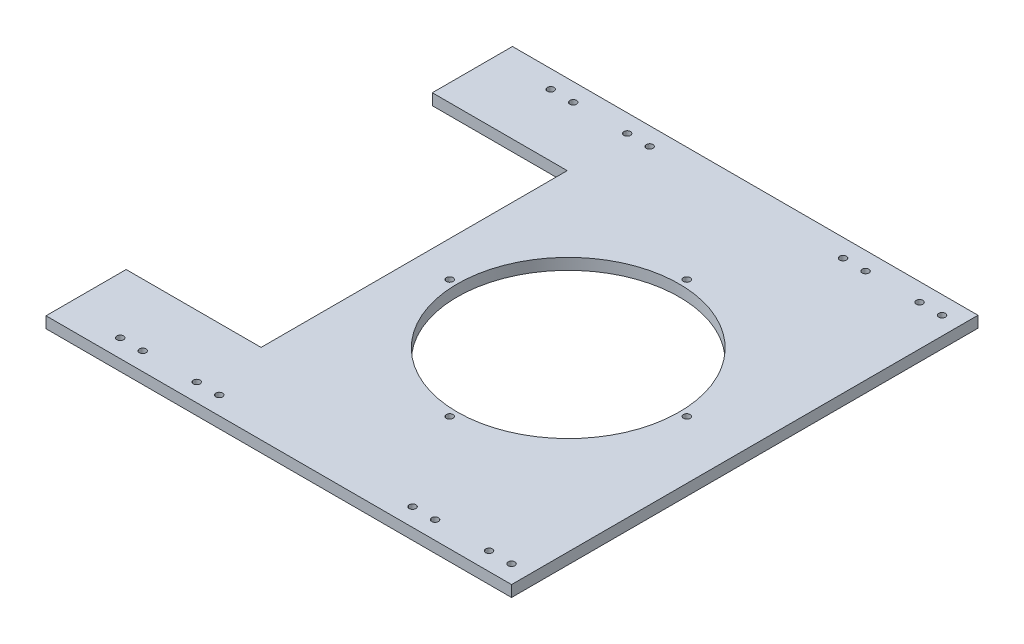
SolidWorks part; units mm, degrees
ref_plane "Front Plane" through (0, 0, 0) normal (0, 0, 1) x (1, 0, 0)
ref_plane "Top Plane" through (0, 0, 0) normal (0, 1, 0) x (1, 0, 0)
ref_plane "Right Plane" through (0, 0, 0) normal (1, 0, 0) x (0, 0, -1)
sketch "Sketch1" plane through (0, 0, 0) normal (0, 1, 0) x (1, 0, 0)
  line L1 (131.445, -131.7003) -> (-131.445, -131.7003)
  line L2 (131.445, -131.7003) -> (131.445, 131.7003)
  line L3 (131.445, 131.7003) -> (-131.445, 131.7003)
  line L4 (-131.445, -131.7003) -> (-131.445, 131.7003)
  line L5 (131.445, -131.7003) -> (-131.445, 131.7003) construction
  line L6 (131.445, 131.7003) -> (-131.445, -131.7003) construction
  circle A0 centre (31.75, 0) radius 62.6745
  point P0 (0, 0)
  dimension "D3" = 125.349
  dimension "D4" = 31.75
  dimension "D1" = 262.89
  dimension "D2" = 263.4005
extrude "Boss-Extrude1" add sketch "Sketch1" along normal blind 6.35
hole_wizard "#6 Clearance Hole1" positions "Sketch2" profile "Sketch3" hole size "#6" standard "ANSI Inch" end condition through all
sketch "Sketch2" plane through (0, 6.35, 0) normal (0, 1, 0) x (1, 0, 0)
  circle A0 centre (31.75, 0) radius 66.9468
  point P0 (31.75, 66.9468)
  point P2 (-35.1968, 0)
  point P4 (98.6968, 0)
  point P6 (31.75, -66.9468)
  point P11 (-35.1968, 0)
  point P12 (31.75, 66.9468)
  point P13 (98.6968, 0)
  point P14 (31.75, -66.9468)
  dimension "D1" = 133.8936
sketch "Sketch3" plane through (31.75, 6.35, -66.9468) normal (1, 0, 0) x (0, 0, 1)
  line L0 (0, 0) -> (0, 6.35)
  line L1 (0, 6.35) -> (1.8986, 6.35)
  line L2 (1.8986, 6.35) -> (1.8986, 0)
  line L5 (1.8986, 0) -> (0, 0)
  line L11 (0, -6.35) -> (0, 107.95) construction
  dimension "Thru Hole Dia." = 3.7973
  dimension "Thru Hole Depth" = 6.35
hole_wizard "#6 Clearance Hole2" positions "Sketch6" profile "Sketch5" hole size "#6" standard "ANSI Inch" end condition through all
sketch "Sketch6" plane through (0, 6.35, 0) normal (0, 1, 0) x (1, 0, 0)
  line L0 (65.405, -121.5403) -> (78.105, -121.5403)
  line L2 (108.585, -121.5403) -> (121.285, -121.5403)
  line L4 (131.445, -131.7003) -> (131.445, 131.7003) construction
  line L5 (-131.445, -131.7003) -> (131.445, -131.7003) construction
  point P0 (121.285, -121.5403)
  point P2 (108.585, -121.5403)
  point P4 (78.105, -121.5403)
  point P6 (65.405, -121.5403)
  dimension "D1" = 12.7
  dimension "D2" = 12.7
  dimension "D3" = 10.16
  dimension "D4" = 30.48
  dimension "D5" = 10.16
  dimension "D6" = 10.16
sketch "Sketch5" plane through (121.285, 6.35, 121.5403) normal (1, 0, 0) x (0, 0, 1)
  line L0 (0, 0) -> (0, 6.35)
  line L1 (0, 6.35) -> (1.8986, 6.35)
  line L2 (1.8986, 6.35) -> (1.8986, 0)
  line L5 (1.8986, 0) -> (0, 0)
  line L11 (0, -6.35) -> (0, 107.95) construction
  dimension "Thru Hole Dia." = 3.7973
  dimension "Thru Hole Depth" = 6.35
mirror "Mirror1" about plane through (0, 0, 0) normal (0, 0, 1) of "#6 Clearance Hole2"
hole_wizard "#6 Clearance Hole3" positions "Sketch7" profile "Sketch8" hole size "#6" standard "ANSI Inch" end condition through all
sketch "Sketch7" plane through (0, 6.35, 0) normal (0, 1, 0) x (1, 0, 0)
  line L0 (-99.695, -121.5403) -> (-86.995, -121.5403)
  line L2 (-56.515, -121.5403) -> (-43.815, -121.5403)
  line L4 (-131.445, -131.7003) -> (131.445, -131.7003) construction
  circle A0 centre (65.405, -121.5403) radius 1.8986 construction
  point P0 (-43.815, -121.5403)
  point P2 (-56.515, -121.5403)
  point P4 (-86.995, -121.5403)
  point P6 (-99.695, -121.5403)
  dimension "D1" = 12.7
  dimension "D2" = 12.7
  dimension "D3" = 109.22
  dimension "D4" = 10.16
  dimension "D5" = 10.16
  dimension "D6" = 30.48
sketch "Sketch8" plane through (-43.815, 6.35, 121.5403) normal (1, 0, 0) x (0, 0, 1)
  line L0 (0, 0) -> (0, 6.35)
  line L1 (0, 6.35) -> (1.8986, 6.35)
  line L2 (1.8986, 6.35) -> (1.8986, 0)
  line L5 (1.8986, 0) -> (0, 0)
  line L11 (0, -6.35) -> (0, 107.95) construction
  dimension "Thru Hole Dia." = 3.7973
  dimension "Thru Hole Depth" = 6.35
mirror "Mirror2" about plane through (0, 0, 0) normal (0, 0, 1) of "#6 Clearance Hole3"
sketch "Sketch9" plane through (0, 6.35, 0) normal (0, 1, 0) x (1, 0, 0)
  line L0 (-131.445, 131.7003) -> (-131.445, -131.7003) construction
  line L1 (-55.245, -86.444) -> (-131.445, -86.444)
  line L2 (-55.245, -86.444) -> (-55.245, 86.444)
  line L3 (-55.245, 86.444) -> (-131.445, 86.444)
  line L4 (-131.445, -86.444) -> (-131.445, 86.444)
  line L5 (-55.245, -86.444) -> (-131.445, 86.444) construction
  line L6 (-55.245, 86.444) -> (-131.445, -86.444) construction
  point P0 (-93.345, 0)
  dimension "D1" = 0
  dimension "D2" = 76.2
extrude "Cut-Extrude1" cut sketch "Sketch9" against normal blind 7.62
